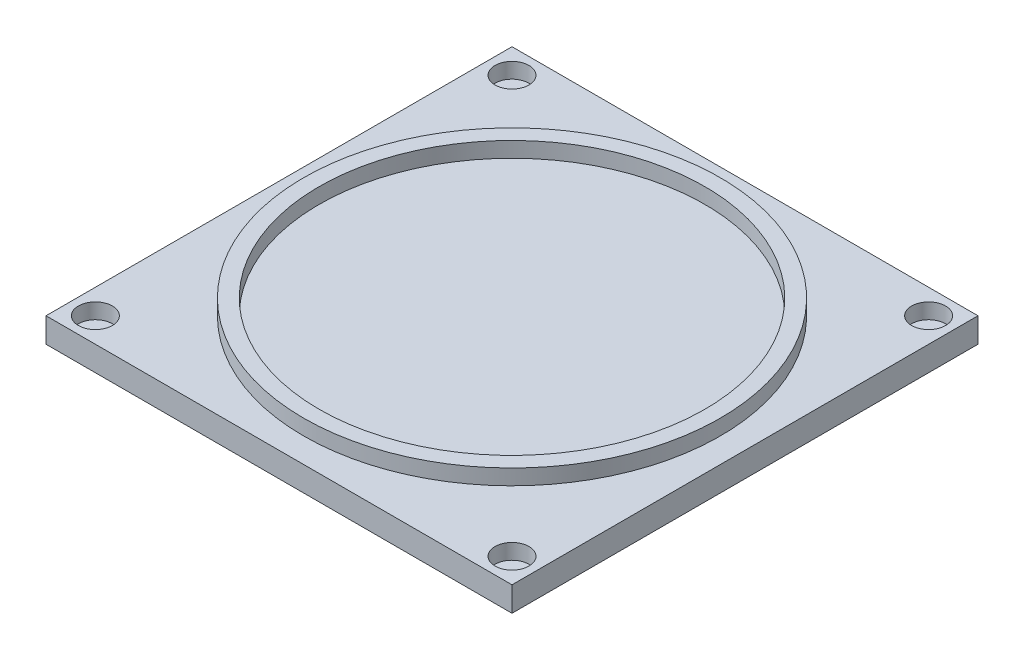
SolidWorks part; units mm, degrees
ref_plane "Front Plane" through (0, 0, 0) normal (0, 0, 1) x (1, 0, 0)
ref_plane "Top Plane" through (0, 0, 0) normal (0, 1, 0) x (1, 0, 0)
ref_plane "Right Plane" through (0, 0, 0) normal (1, 0, 0) x (0, 0, -1)
sketch "Sketch1" plane through (0, 0, 0) normal (0, 1, 0) x (1, 0, 0)
  line L1 (-42.2989, -4.339) -> (-12.0989, -4.339)
  line L2 (-42.2989, -4.339) -> (-42.2989, -34.539)
  line L3 (-42.2989, -34.539) -> (-12.0989, -34.539)
  line L4 (-12.0989, -4.339) -> (-12.0989, -34.539)
extrude "Boss-Extrude1" add sketch "Sketch1" along normal blind 1.6
sketch "Sketch2" plane through (0, 1.6, 0) normal (0, 1, 0) x (1, 0, 0)
  circle A0 centre (-27.1989, -19.439) radius 13.5
  circle A1 centre (-27.1989, -19.439) radius 12.5
extrude "Boss-Extrude2" add sketch "Sketch2" along normal blind 1
sketch "Sketch3" plane through (0, 1.6, 0) normal (0, 1, 0) x (1, 0, 0)
  circle A0 centre (-40.6989, -32.939) radius 1.1
  circle A1 centre (-13.6989, -32.939) radius 1.1
  circle A2 centre (-13.6989, -5.939) radius 1.1
  circle A3 centre (-40.6989, -5.939) radius 1.1
extrude "Cut-Extrude1" cut sketch "Sketch3" against normal blind 1
